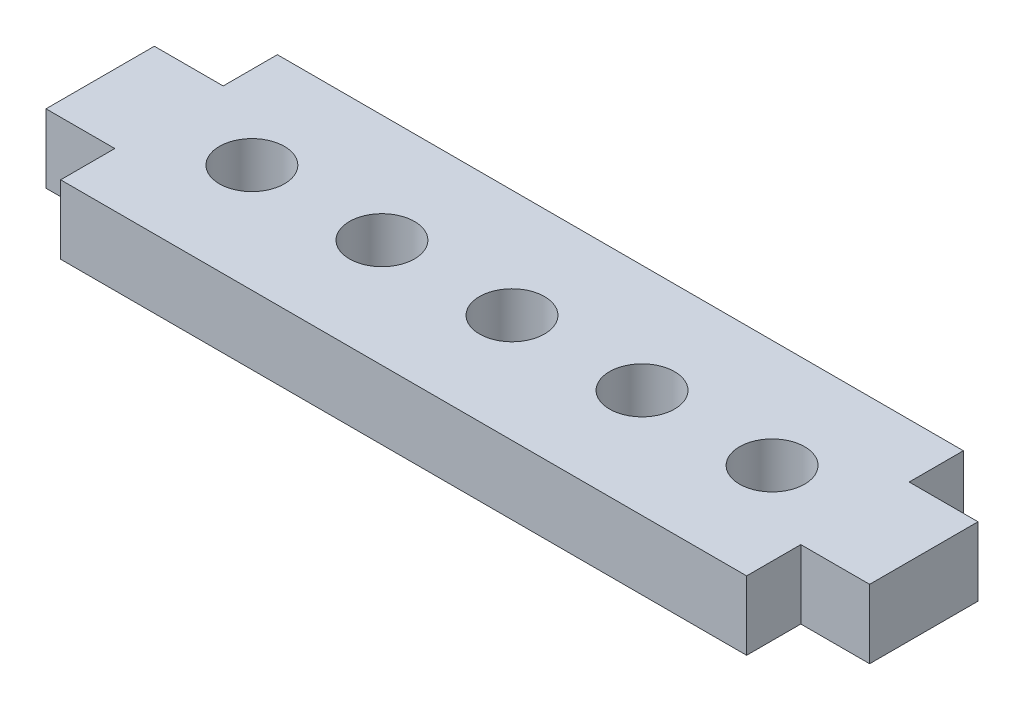
SolidWorks part; units mm, degrees
material "Balsa"
ref_plane "Front Plane" through (0, 0, 0) normal (0, 0, 1) x (1, 0, 0)
ref_plane "Top Plane" through (0, 0, 0) normal (0, 1, 0) x (1, 0, 0)
ref_plane "Right Plane" through (0, 0, 0) normal (1, 0, 0) x (0, 0, -1)
sketch "Sketch1" plane through (0, 0, 0) normal (0, 1, 0) x (1, 0, 0)
  line L0 (7.65, 10) -> (19.65, 10) construction
  line L1 (0, 0) -> (63.3, 0)
  line L2 (0, 0) -> (0, 5)
  line L3 (0, 20) -> (63.3, 20)
  line L4 (63.3, 0) -> (63.3, 5)
  line L5 (19.65, 10) -> (31.65, 10) construction
  line L6 (31.65, 10) -> (43.65, 10) construction
  line L7 (31.65, 0) -> (31.65, 20) construction
  line L8 (0, 15) -> (-6.35, 15)
  line L9 (-6.35, 15) -> (-6.35, 5)
  line L10 (-6.35, 5) -> (0, 5)
  line L11 (0, 15) -> (0, 20)
  line L12 (63.3, 15) -> (69.65, 15)
  line L13 (69.65, 15) -> (69.65, 5)
  line L14 (69.65, 5) -> (63.3, 5)
  line L15 (63.3, 15) -> (63.3, 20)
  line L16 (43.65, 10) -> (55.65, 10) construction
  circle A0 centre (7.65, 10) radius 3
  circle A1 centre (19.65, 10) radius 3
  circle A2 centre (31.65, 10) radius 3
  circle A3 centre (43.65, 10) radius 3
  circle A4 centre (55.65, 10) radius 3
  point P15 (31.65, 10)
  point P16 (0, 0)
  point P25 (-6.35, 10)
  point P26 (69.65, 10)
  point P29 (10, 10)
  point P30 (0, 0)
  dimension "D2" = 6
  dimension "D1" = 12
  dimension "D3" = 76
  dimension "D5" = 6.35
  dimension "D6" = 10
extrude "Boss-Extrude1" add sketch "Sketch1" along normal blind 6.35
